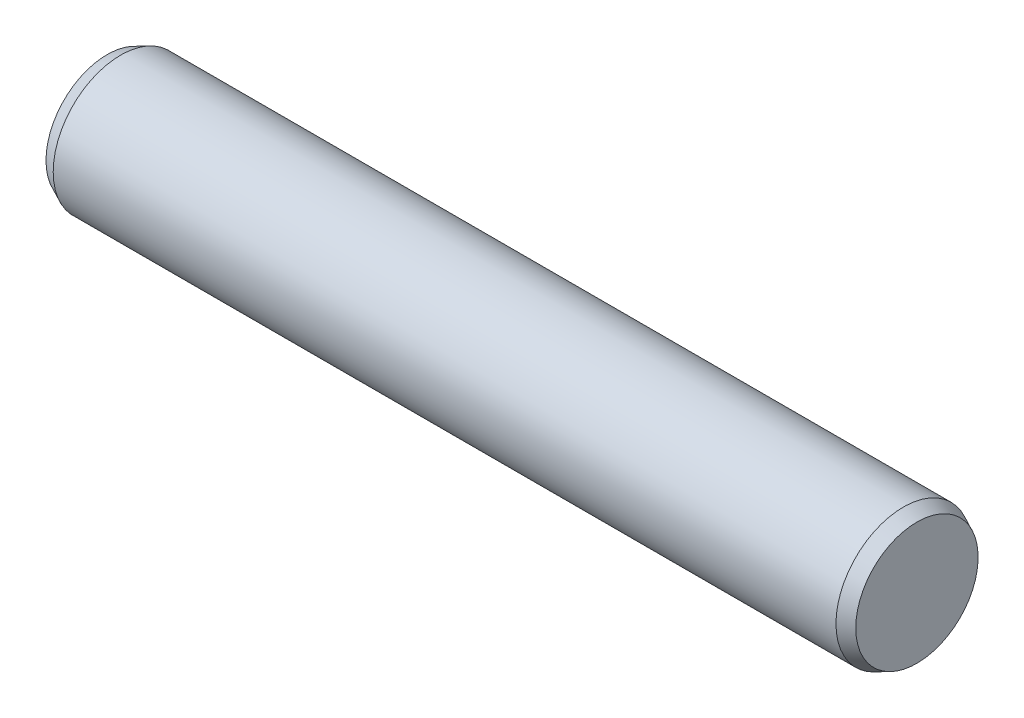
SolidWorks part; units mm, degrees
ref_plane "Plane1" through (0, 0, 0) normal (0, 0, 1) x (1, 0, 0)
ref_plane "Plane2" through (0, 0, 0) normal (0, 1, 0) x (1, 0, 0)
ref_plane "Plane3" through (0, 0, 0) normal (1, 0, 0) x (0, 0, -1)
sketch "Sketch1" plane through (0, 0, 0) normal (0, 0, 1) x (1, 0, 0)
  line L1 (-6.35, 0) -> (107.95, 0) construction
  line L2 (0, 0) -> (38.1, 0)
  line L3 (38.1, 0) -> (38.1, 2.8789)
  line L4 (38.1, 2.8789) -> (37.465, 3.175)
  line L5 (37.465, 3.175) -> (0.635, 3.175)
  line L6 (0, 2.8789) -> (0, 0)
  line L7 (0.635, 3.175) -> (0, 2.8789)
  dimension "D1" = 25
  dimension "D2" = 0.635
  dimension "D3" = 25
  dimension "Diameter" = 6.35
  dimension "Length" = 38.1
  dimension "Chamfer_length" = 0.635
revolve "Base-Revolve" add sketch "Sketch1" angle 360 about L1
equation "\"D2@Sketch1\" = \"Chamfer_length@Sketch1\""
